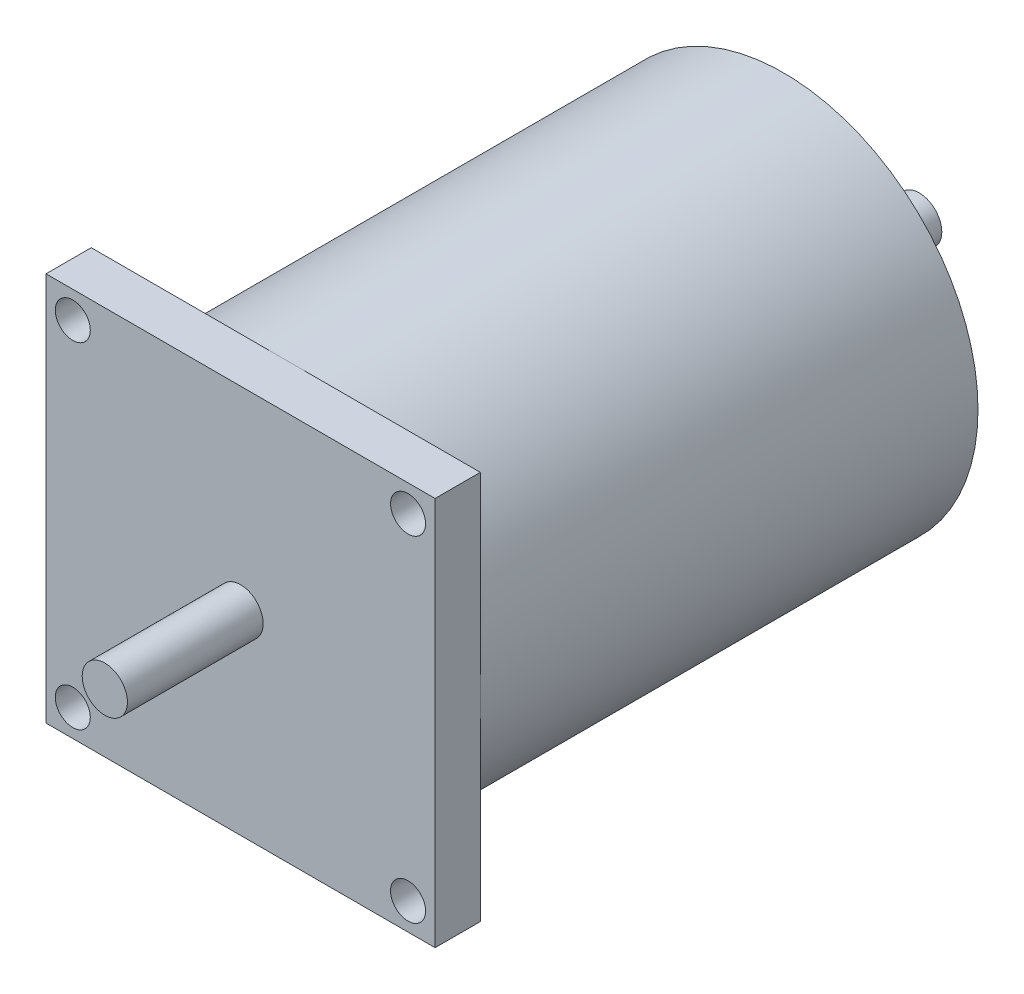
SolidWorks part; units mm, degrees
ref_plane "Front Plane" through (0, 0, 0) normal (0, 0, 1) x (1, 0, 0)
ref_plane "Top Plane" through (0, 0, 0) normal (0, 1, 0) x (1, 0, 0)
ref_plane "Right Plane" through (0, 0, 0) normal (1, 0, 0) x (0, 0, -1)
sketch "Sketch1" plane through (0, 0, 0) normal (0, 0, 1) x (1, 0, 0)
  line L1 (-27.305, 27.305) -> (27.305, 27.305)
  line L2 (-27.305, 27.305) -> (-27.305, -27.305)
  line L3 (-27.305, -27.305) -> (27.305, -27.305)
  line L4 (27.305, 27.305) -> (27.305, -27.305)
  dimension "D1" = 27.305
  dimension "D2" = 54.61
  dimension "D3" = 27.305
  dimension "D4" = 54.61
extrude "Boss-Extrude1" add sketch "Sketch1" along normal blind 6.35
hole_wizard "#10 (0.1935) Diameter Hole1" positions "Sketch5" profile "Sketch6" hole size "#10" standard "ANSI Inch" end condition through all
sketch "Sketch5" plane through (0, 0, 6.35) normal (0, 0, 1) x (1, 0, 0)
  line L0 (-27.305, 27.305) -> (-27.305, -27.305) construction
  line L2 (27.305, 27.305) -> (-27.305, 27.305) construction
  line L3 (-0.0175, 0.0175) -> (-23.5458, 23.5458) construction
  point P0 (-23.5458, 23.5458)
  point P21 (23.5107, 23.5458)
  point P22 (23.5107, -23.5107)
  point P23 (-23.5458, -23.5107)
  dimension "D1" = 3.7592
  dimension "D2" = 3.7592
  dimension "D4" = 33.274
  dimension "D3" = 4
sketch "Sketch6" plane through (-23.5458, 23.5458, 6.35) normal (1, 0, 0) x (0, -1, 0)
  line L0 (0, 0) -> (0, 6.35)
  line L1 (0, 6.35) -> (2.4574, 6.35)
  line L2 (2.4574, 6.35) -> (2.4574, 0)
  line L5 (2.4574, 0) -> (0, 0)
  line L11 (0, -6.35) -> (0, 107.95) construction
  dimension "Thru Hole Dia." = 4.9149
  dimension "Thru Hole Depth" = 6.35
sketch "Sketch7" plane through (0, 0, 0) normal (0, 0, -1) x (-1, 0, 0)
  circle A0 centre (0, 0) radius 27.305
extrude "Boss-Extrude2" add sketch "Sketch7" along normal blind 69.85
sketch "Sketch8" plane through (0, 0, -69.85) normal (0, 0, -1) x (-1, 0, 0)
  circle A0 centre (0, 0) radius 3.175
  dimension "D1" = 6.35
extrude "Boss-Extrude3" add sketch "Sketch8" along normal blind 19.05
sketch "Sketch9" plane through (0, 0, 6.35) normal (0, 0, 1) x (1, 0, 0)
  circle A0 centre (0, 0) radius 3.175
  dimension "D1" = 6.35
extrude "Boss-Extrude4" add sketch "Sketch9" along normal blind 19.05
